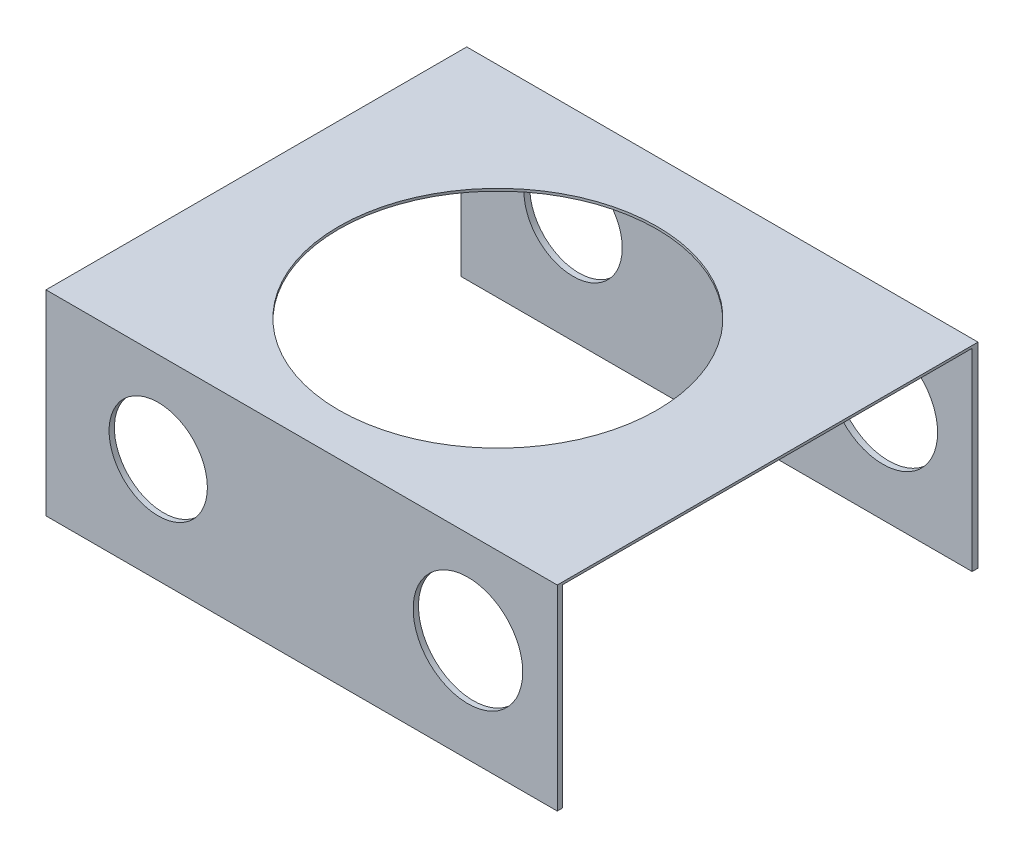
SolidWorks part; units mm, degrees
ref_plane "Front Plane" through (0, 0, 0) normal (0, 0, 1) x (1, 0, 0)
ref_plane "Top Plane" through (0, 0, 0) normal (0, 1, 0) x (1, 0, 0)
ref_plane "Right Plane" through (0, 0, 0) normal (1, 0, 0) x (0, 0, -1)
sketch "Sketch1" plane through (0, 0, 0) normal (0, 1, 0) x (1, 0, 0)
  line L33 (-15.4451, 38.452) -> (-43.6751, 38.452)
  line L53 (-47.2454, 39.5079) -> (46.7439, 39.5079)
  line L54 (17.6169, -35.1748) -> (45.755, -35.1748)
  line L55 (-47.2454, 39.5079) -> (-47.2454, -36.1311)
  line L56 (-47.2454, -36.1311) -> (46.7439, -36.1311)
  line L62 (46.7439, 39.5079) -> (46.7439, -36.1311)
  line L63 (-15.3758, -35.1748) -> (-46.245, -35.1748)
  line L76 (17.1649, 38.452) -> (43.185, 38.452)
  line L83 (43.185, 38.452) -> (45.755, 38.452)
  line L84 (45.755, 32.4552) -> (45.755, 32.4539)
  line L85 (-43.6751, 38.452) -> (-46.245, 38.452)
  line L86 (-46.245, 38.452) -> (-46.245, -35.1748)
  line L87 (45.755, 38.452) -> (45.755, -35.1748)
  line L88 (17.1649, 38.452) -> (-15.4757, 38.452)
  line L89 (17.6169, -35.1748) -> (-15.3758, -35.1748)
  circle A15 centre (-0.1268, 0.0623) radius 28.6056
  point P29 (-46.1871, -35.1748)
sketch "Sketch7" plane through (0, 0, 0) normal (1, 0, 0) x (0, 0, -1)
  line L2 (-35.1748, 19.7617) -> (-35.1748, -26.2383)
  line L4 (38.452, 19.7617) -> (38.452, -26.2383)
  line L5 (-35.1748, 19.7617) -> (38.452, 19.7617)
  line L6 (-35.1748, -26.2383) -> (38.452, -26.2383)
  point P1 (0, 0)
  point P7 (-35.1748, -3.2383)
  point P8 (38.452, -3.2383)
  point P9 (1.6386, 19.7617)
  point P12 (1.6386, -26.2383)
extrude "Boss-Extrude1" add sketch "Sketch1" along normal blind 20.2 and the other way blind 15 contours L89 L54 L87 L84 L83 L76 L88 L33 L85 L86 L63 A15 | L62 L53 L55 L56 L54 L89 L63 L86 L85 L33 L88 L76 L83 L87 L84
extrude "Cut-Extrude1" cut sketch "Sketch7" against normal through all both and the other way through all
sketch "Sketch8" plane through (0, 20.2, 0) normal (0, 1, 0) x (1, 0, 0)
  line L0 (-45.1711, 40.3653) -> (-45.1711, -47.0761)
  line M4 (46.7439, 39.5079) -> (-47.2454, 39.5079)
  line M5 (-47.2454, 39.5079) -> (-47.2454, -36.1311)
  line M6 (-47.2454, -36.1311) -> (46.7439, -36.1311)
extrude "Cut-Extrude2" cut sketch "Sketch8" against normal through all both and the other way through all contours L0 M4 M5 M6
sketch "Sketch9" plane through (0, 0, 36.1311) normal (0, 0, 1) x (1, 0, 0)
  circle A0 centre (30.6864, 3.5313) radius 9.8522
  circle A1 centre (-24.9962, 3.9234) radius 8.8366
  point P4 (-24.9962, 3.9234)
  point P5 (30.6864, 3.5313)
extrude "Cut-Extrude3" cut sketch "Sketch9" against normal through all both
